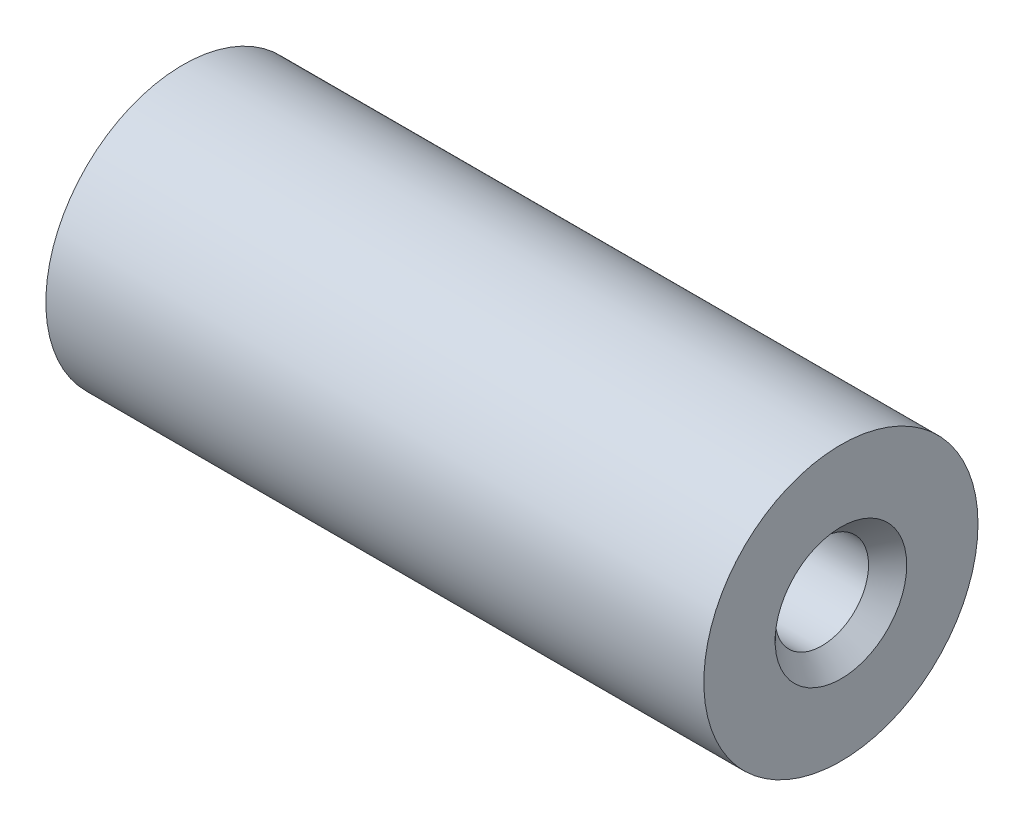
SolidWorks part; units mm, degrees
material "6061-T6 (SS)"
ref_plane "Front Plane" through (0, 0, 0) normal (0, 0, 1) x (1, 0, 0)
ref_plane "Top Plane" through (0, 0, 0) normal (0, 1, 0) x (1, 0, 0)
ref_plane "Right Plane" through (0, 0, 0) normal (1, 0, 0) x (0, 0, -1)
sketch "Sketch1" plane through (0, 0, 0) normal (0, 0, 1) x (1, 0, 0)
  line L0 (0, 0) -> (-8.9681, 0) construction
  line L1 (0, 0) -> (38.1, 0)
  line L2 (0, 0) -> (0, 7.9375)
  line L3 (0, 7.9375) -> (38.1, 7.9375)
  line L4 (38.1, 0) -> (38.1, 7.9375)
  dimension "D1" = 15.875
  dimension "D2" = 38.1
revolve "Revolve1" add sketch "Sketch1" angle 360 about L0
hole_wizard "1/4-28 Tapped Hole1" positions "Sketch2" profile "Sketch3" tap size "1/4-28" standard "ANSI Inch"
sketch "Sketch2" plane through (38.1, 0, 0) normal (1, 0, 0) x (0, 0, -1)
  point P0 (0, 0)
sketch "Sketch3" plane through (38.1, 0, 0) normal (0, 1, 0) x (0, 0, -1)
  line L0 (0, 0) -> (0, 14.3254)
  line L1 (0, 14.3254) -> (2.7051, 12.7)
  line L2 (2.7051, 12.7) -> (2.7051, 1.1049)
  line L3 (2.7051, 1.1049) -> (3.81, 0)
  line L5 (3.81, 0) -> (0, 0)
  line L6 (-2.7051, 1.1049) -> (-3.81, 0) construction
  line L10 (0, 14.3254) -> (-2.7051, 12.7) construction
  line L11 (0, -6.35) -> (0, 107.95) construction
  dimension "Tap Drill Dia." = 5.4102
  dimension "Tap Drill Depth" = 12.7
  dimension "Near C'Sink Dia." = 7.62
  dimension "Near C'Sink Angle" = 90
  dimension "Drill Angle" = 118
cosmetic thread "Hole Thread1" parameters "D1"=19.05, "D2"=6.35
hole_wizard "7/16-28 Tapped Hole" positions "Sketch4" profile "Sketch5" tap size "5/16-24" standard "ANSI Inch"
sketch "Sketch4" plane through (0, 0, 0) normal (-1, 0, 0) x (0, 0, 1)
  point P0 (0, 0)
sketch "Sketch5" plane through (0, 0, 0) normal (0, 1, 0) x (0, 0, 1)
  line L0 (0, 0) -> (0, 14.7756)
  line L1 (0, 14.7756) -> (3.4544, 12.7)
  line L2 (3.4544, 12.7) -> (3.4544, 1.1493)
  line L3 (3.4544, 1.1493) -> (4.6037, 0)
  line L5 (4.6037, 0) -> (0, 0)
  line L6 (-3.4544, 1.1493) -> (-4.6037, 0) construction
  line L10 (0, 14.7756) -> (-3.4544, 12.7) construction
  line L11 (0, -6.35) -> (0, 107.95) construction
  dimension "Tap Drill Dia." = 6.9088
  dimension "Tap Drill Depth" = 12.7
  dimension "Near C'Sink Dia." = 9.2075
  dimension "Near C'Sink Angle" = 90
  dimension "Drill Angle" = 118
cosmetic thread "Hole Thread2" parameters "D1"=16.002, "D2"=7.9375
ref_plane "Stroke Mate" through (12.7, 0, 0) normal (1, 0, 0) x (0, 0, -1)
